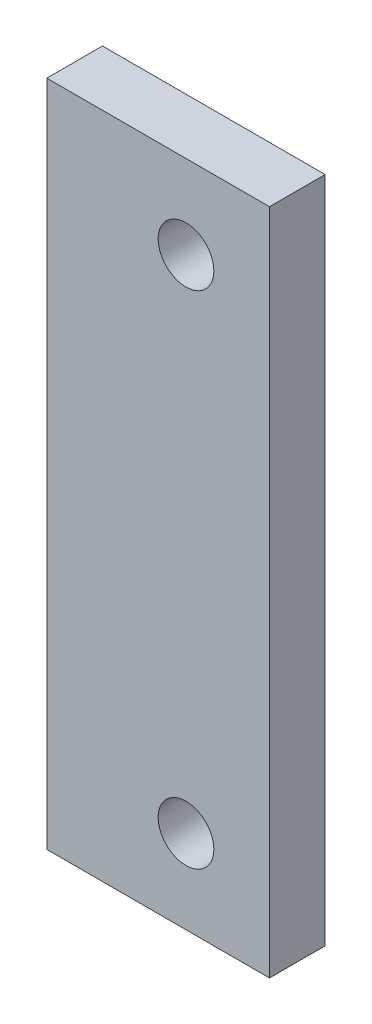
SolidWorks part; units mm, degrees
ref_plane "Front Plane" through (0, 0, 0) normal (0, 0, 1) x (1, 0, 0)
ref_plane "Top Plane" through (0, 0, 0) normal (0, 1, 0) x (1, 0, 0)
ref_plane "Right Plane" through (0, 0, 0) normal (1, 0, 0) x (0, 0, -1)
sketch "Sketch1" plane through (0, 0, 0) normal (0, 0, 1) x (1, 0, 0)
  line L0 (30, -215) -> (30, -385) construction
  line L1 (30, -240) -> (-10, -240)
  line L2 (30, -240) -> (30, -360)
  line L3 (30, -360) -> (-10, -360)
  line L4 (-10, -240) -> (-10, -360)
  line L5 (37, -300) -> (1897.553, -300) construction
  dimension "D1" = 120
  dimension "D2" = 40
  dimension "D3" = 60
extrude "Boss-Extrude1" add sketch "Sketch1" along normal blind 10
sketch "Sketch2" plane through (0, 0, 0) normal (0, 0, 1) x (1, 0, 0)
  line L0 (15, -233.4943) -> (15, -370.6188) construction
  line L1 (15, -200) -> (15, -400) construction
  line L2 (62.9406, -300) -> (-15.6748, -300) construction
  line L3 (37, -300) -> (1897.553, -300) construction
  circle A0 centre (15, -255) radius 5
  circle A1 centre (15, -345) radius 5
  dimension "D1" = 10
  dimension "D2" = 10
  dimension "D3" = 45
  dimension "D4" = 45
extrude "Cut-Extrude2" cut sketch "Sketch2" along normal through all
